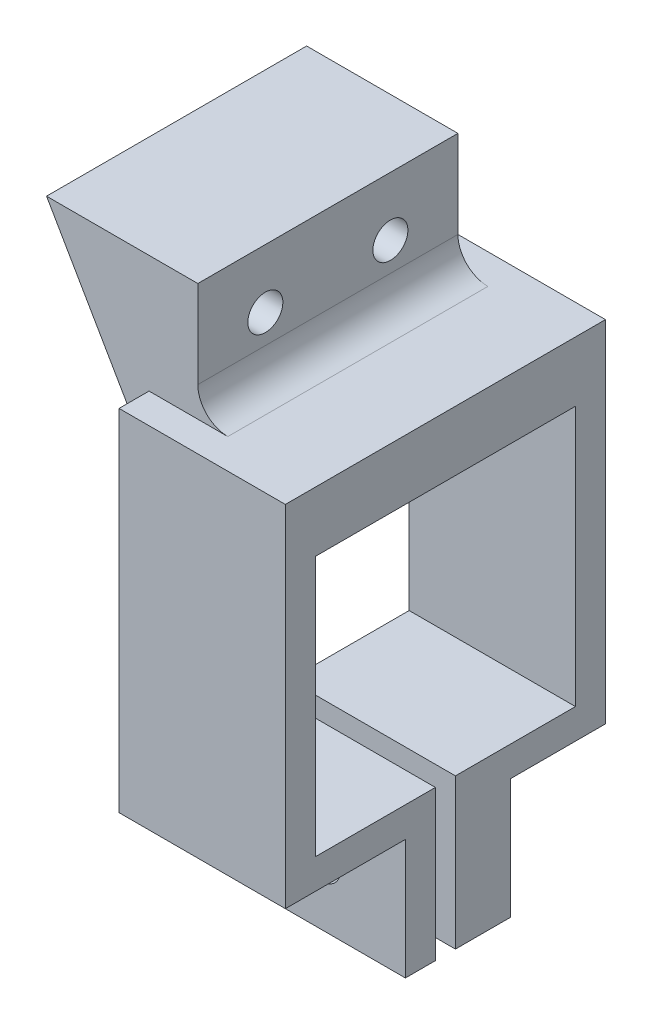
SolidWorks part; units mm, degrees
ref_plane "Front Plane" through (0, 0, 0) normal (0, 0, 1) x (1, 0, 0)
ref_plane "Top Plane" through (0, 0, 0) normal (0, 1, 0) x (1, 0, 0)
ref_plane "Right Plane" through (0, 0, 0) normal (1, 0, 0) x (0, 0, -1)
sketch "Sketch1" plane through (0, 0, 0) normal (0, 0, 1) x (1, 0, 0)
  line L0 (0, 0) -> (-10.248, 17.75)
  line L1 (-10.248, 17.75) -> (4.876, 17.75)
  line L2 (4.876, 17.75) -> (4.876, 6)
  line L3 (4.876, 6) -> (16.626, 6)
  line L4 (16.626, 6) -> (16.626, 0)
  line L5 (16.626, 0) -> (0, 0)
  line L6 (-10.248, 17.75) -> (-17.1762, 17.75) construction
  line L7 (-17.1762, 17.75) -> (-6.9282, 0) construction
  line L8 (-6.9282, 0) -> (0, 0) construction
  line L9 (4.876, 13) -> (-14.4338, 13) construction
  line L10 (-5.124, 8.875) -> (4.876, 8.875) construction
  dimension "D2" = 10
  dimension "D1" = 120
  dimension "D3" = 6
  dimension "D4" = 7
  dimension "D5" = 4.75
  dimension "D6" = 11.75
  dimension "D7" = 6
extrude "Boss-Extrude1" add sketch "Sketch1" along normal blind 26
sketch "Sketch3" plane through (4.876, 0, 0) normal (1, 0, 0) x (0, 0, -1)
  line L0 (-26, 11.875) -> (-19.25, 11.875) construction
  line L1 (-26, 6) -> (-26, 17.75) construction
  line L2 (-19.25, 11.875) -> (-6.75, 11.875) construction
  line L3 (-6.75, 11.875) -> (0, 11.875) construction
  line L4 (0, 6) -> (0, 17.75) construction
  circle A0 centre (-19.25, 11.875) radius 1.75
  circle A1 centre (-6.75, 11.875) radius 1.75
  dimension "D1" = 12.5
  dimension "3mm Hole" = 3.5
extrude "Cut-Extrude2" cut sketch "Sketch3" along direction (-1, 0, 0) on the side against the normal through all
fillet "Fillet1" radius 3 1 edges at (4.876, 6, 13)
sketch "Sketch4" plane through (16.626, 0, 0) normal (1, 0, 0) x (0, 0, -1)
  line L1 (-26, 6) -> (-29, 6)
  line L2 (-29, 6) -> (-29, -29)
  line L3 (-29, -29) -> (-17, -29)
  line L4 (-17, -29) -> (-17, -41)
  line L5 (-17, -41) -> (-14, -41)
  line L6 (-14, -41) -> (-14, -26)
  line L7 (-14, -26) -> (-26, -26)
  line L8 (-26, 6) -> (-26, 0)
  line L9 (-26, 0) -> (0, 0) construction
  line L10 (-26, -26) -> (-26, -29) construction
  line L11 (-13, 0) -> (-13, -46.26) construction
  line L12 (-26, 0) -> (-26, -26)
  dimension "D2" = 3
  dimension "D3" = 12
  dimension "D4" = 2
extrude "Boss-Extrude2" add sketch "Sketch4" against normal up to vertex (16.626 mm away) up to point (0, 0, 26)
ref_plane "Plane1" through (0, 0, 13) normal (0, 0, -1) x (-1, 0, 0)
mirror "Mirror1" about plane through (0, 0, 13) normal (0, 0, -1) of "Boss-Extrude2"
sketch "Sketch5" plane through (0, 0, 17) normal (0, 0, 1) x (1, 0, 0)
  line L0 (0, -41) -> (16.626, -29) construction
  circle A0 centre (8.313, -35) radius 1.8
  dimension "D1" = 3.6
extrude "Cut-Extrude3" cut sketch "Sketch5" against normal through all
sketch "Sketch6" plane through (0, 0, 9) normal (0, 0, -1) x (-1, 0, 0)
  line L1 (-5.513, -33.3834) -> (-8.313, -31.7668)
  line L2 (-8.313, -31.7668) -> (-11.113, -33.3834)
  line L3 (-11.113, -33.3834) -> (-11.113, -36.6166)
  line L4 (-16.626, -29) -> (-16.626, -41)
  line L5 (-16.626, -41) -> (0, -41)
  line L6 (0, -41) -> (0, -29)
  line L7 (0, -29) -> (-16.626, -29)
  line L8 (-16.626, -29) -> (-16.626, -41)
  line L9 (-16.626, -41) -> (0, -41)
  line L10 (0, -41) -> (0, -29)
  line L11 (0, -29) -> (-16.626, -29)
  line L12 (-11.113, -36.6166) -> (-8.313, -38.2332)
  line L13 (-8.313, -38.2332) -> (-5.513, -36.6166)
  line L14 (-5.513, -36.6166) -> (-5.513, -33.3834)
  circle A0 centre (-8.313, -35) radius 2.8 construction
  dimension "D2" = 5.6
  dimension "D1" = 0
extrude "Boss-Extrude3" add sketch "Sketch6" along normal blind 2.5
equation "\"1.5.00mm\"=2"
